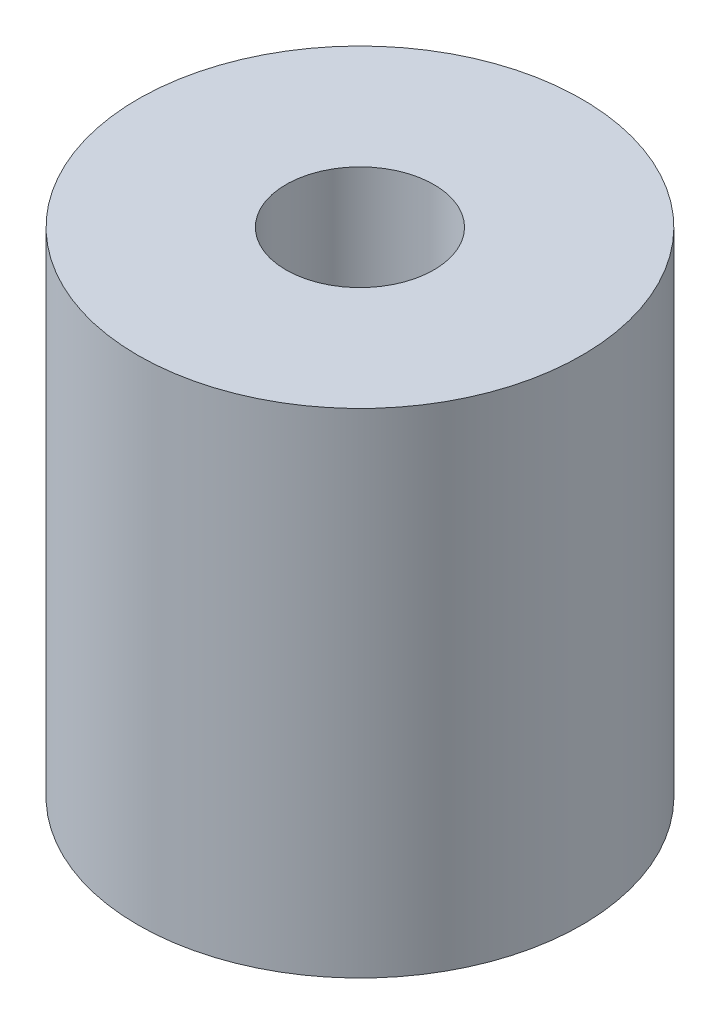
SolidWorks part; units mm, degrees
material "1060 Alloy"
ref_plane "Front Plane" through (0, 0, 0) normal (0, 0, 1) x (1, 0, 0)
ref_plane "Top Plane" through (0, 0, 0) normal (0, 1, 0) x (1, 0, 0)
ref_plane "Right Plane" through (0, 0, 0) normal (1, 0, 0) x (0, 0, -1)
sketch "Sketch1" plane through (0, 0, 0) normal (0, 1, 0) x (1, 0, 0)
  circle A0 centre (0, 0) radius 4.5
  circle A1 centre (0, 0) radius 1.5
extrude "Boss-Extrude1" add sketch "Sketch1" along normal blind 10
